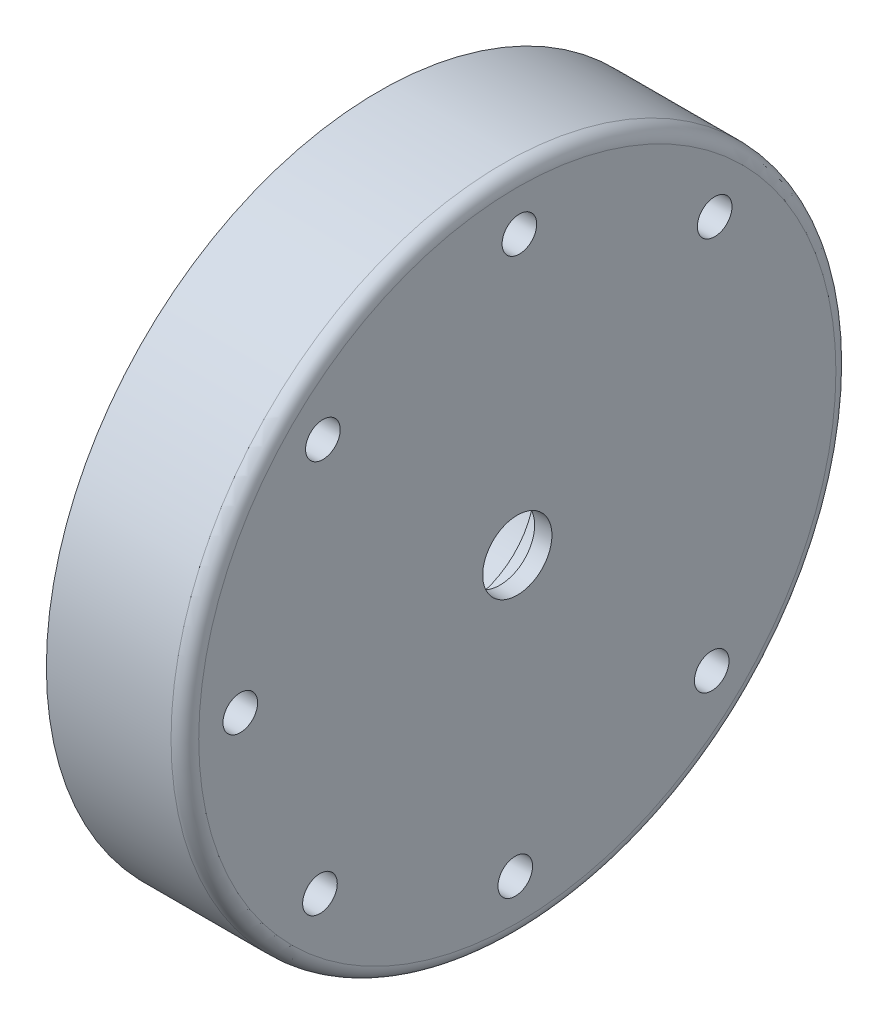
SolidWorks part; units mm, degrees
material "6061 Alloy"
ref_plane "Front Plane" through (0, 0, 0) normal (0, 0, 1) x (1, 0, 0)
ref_plane "Top Plane" through (0, 0, 0) normal (0, 1, 0) x (1, 0, 0)
ref_plane "Right Plane" through (0, 0, 0) normal (1, 0, 0) x (0, 0, -1)
sketch "Sketch1" plane through (0, 0, 0) normal (1, 0, 0) x (0, 0, -1)
  circle A0 centre (0, 0) radius 60.96
extrude "Boss-Extrude1" add sketch "Sketch1" along normal blind 25.4
fillet "Fillet1" radius 2.54 1 edges at (25.4, 0, -60.96)
sketch "Sketch2" plane through (25.4, 0, 0) normal (1, 0, 0) x (0, 0, -1)
  circle A0 centre (0, 0) radius 4.508
extrude "Cut-Extrude1" cut sketch "Sketch2" against normal blind 6.35
sketch "Sketch3" plane through (25.4, 0, 0) normal (1, 0, 0) x (0, 0, -1)
  circle A0 centre (22.5439, 0) radius 3.175
extrude "Cut-Extrude2" [suppressed] cut sketch "Sketch3" against normal blind 19.05
pattern_circular "CirPattern1" [suppressed] count 8 over 360
sketch "Sketch4" plane through (25.4, 0, 0) normal (1, 0, 0) x (0, 0, -1)
  circle A0 centre (0, 0) radius 6.35
  dimension "D1" = 12.7
extrude "Cut-Extrude3" cut sketch "Sketch4" against normal through all
sketch "Sketch5" plane through (0, 0, 0) normal (-1, 0, 0) x (0, 0, 1)
  circle A0 centre (-36.1888, 35.6513) radius 3.175
  dimension "D1" = 50.8
extrude "Cut-Extrude4" cut sketch "Sketch5" against normal through all contours A0
pattern_circular "CirPattern2" count 8 over 360 about axis through (0, 0, 0) along (1, 0, 0) skipping 7 of "Cut-Extrude4"
sketch "Sketch6" plane through (0, 0, 0) normal (-1, 0, 0) x (0, 0, 1)
  circle A0 centre (0, 0) radius 14.605
  dimension "D1" = 29.21
extrude "Cut-Extrude5" cut sketch "Sketch6" against normal offset from surface (22.225 mm away) 3.175 up to face at (25.4, 48.5535, 1.865)
sketch "Sketch7" plane through (22.225, 0, 0) normal (-1, 0, 0) x (0, 0, 1)
  circle A0 centre (0, 0) radius 14.605
  circle A1 centre (0, 0) radius 12.7
  dimension "D1" = 29.21
  dimension "D2" = 25.4
extrude "Boss-Extrude2" add sketch "Sketch7" along normal blind 6.35
sketch "Sketch8" plane through (0, 0, 0) normal (-1, 0, 0) x (0, 0, 1)
  circle A0 centre (0, 0) radius 14.605
  circle A1 centre (0, 0) radius 17.5
  dimension "D1" = 29.21
  dimension "D2" = 34.9999
extrude "Boss-Extrude3" add sketch "Sketch8" along normal blind 8.89
